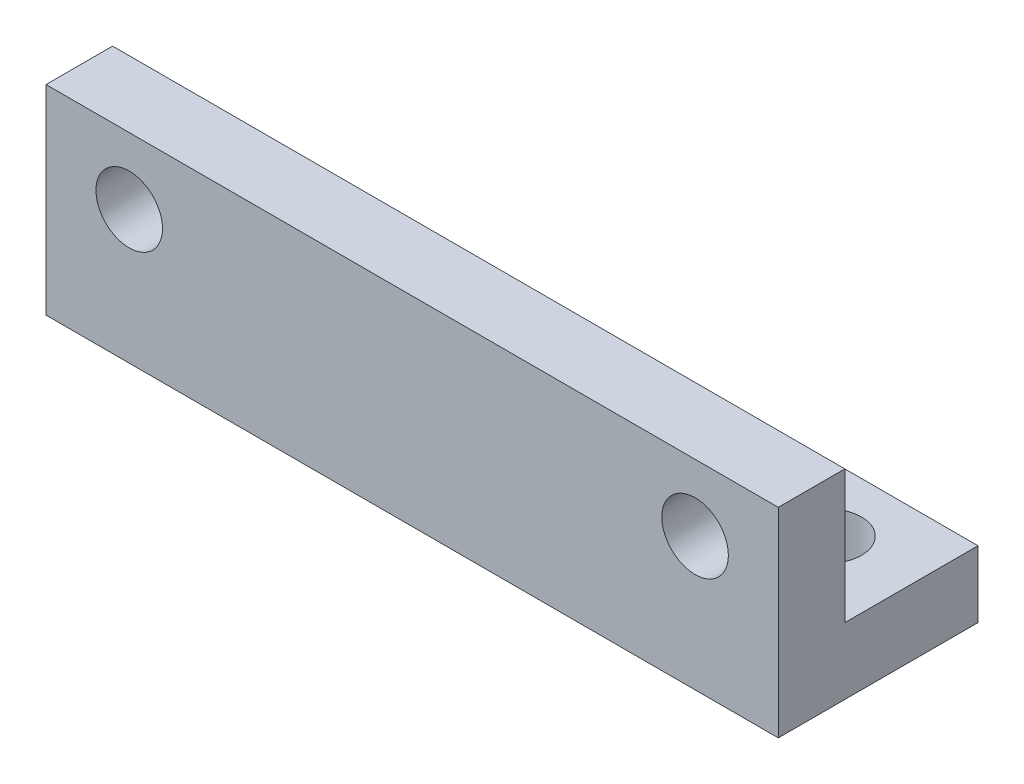
SolidWorks part; units mm, degrees
ref_plane "前视基准面" through (0, 0, 0) normal (0, 0, 1) x (1, 0, 0)
ref_plane "上视基准面" through (0, 0, 0) normal (0, 1, 0) x (1, 0, 0)
ref_plane "右视基准面" through (0, 0, 0) normal (1, 0, 0) x (0, 0, -1)
sketch "草图1" plane through (0, 0, 0) normal (1, 0, 0) x (0, 0, -1)
  line L0 (0, 0) -> (0, 6)
  line L1 (0, 6) -> (2, 6)
  line L2 (2, 6) -> (2, 2)
  line L3 (2, 2) -> (6, 2)
  line L4 (6, 2) -> (6, 0)
  line L5 (6, 0) -> (0, 0)
  dimension "D1" = 2
  dimension "D2" = 2
  dimension "D3" = 6
  dimension "D4" = 6
extrude "凸台-拉伸1" add sketch "草图1" along normal mid plane 22
sketch "草图2" plane through (0, 0, 0) normal (0, 0, 1) x (1, 0, 0)
  line L0 (0, 6) -> (0, 0) construction
  line L1 (11, 6) -> (-11, 6) construction
  line L2 (11, 0) -> (-11, 0) construction
  circle A0 centre (-8.5, 4) radius 1
  circle A1 centre (8.5, 4) radius 1
  dimension "D1" = 2
  dimension "D2" = 8.5
  dimension "D3" = 4
extrude "切除-拉伸1" cut sketch "草图2" against normal up to next
sketch "草图3" plane through (0, 0, 0) normal (0, -1, 0) x (1, 0, 0)
  line L0 (0, 0) -> (0, -6) construction
  line L1 (11, 0) -> (-11, 0) construction
  line L2 (11, -6) -> (-11, -6) construction
  circle A0 centre (-8.5, -4) radius 1
  circle A1 centre (8.5, -4) radius 1
  dimension "D1" = 2
  dimension "D2" = 8.5
  dimension "D3" = 4
extrude "切除-拉伸2" cut sketch "草图3" against normal up to next
